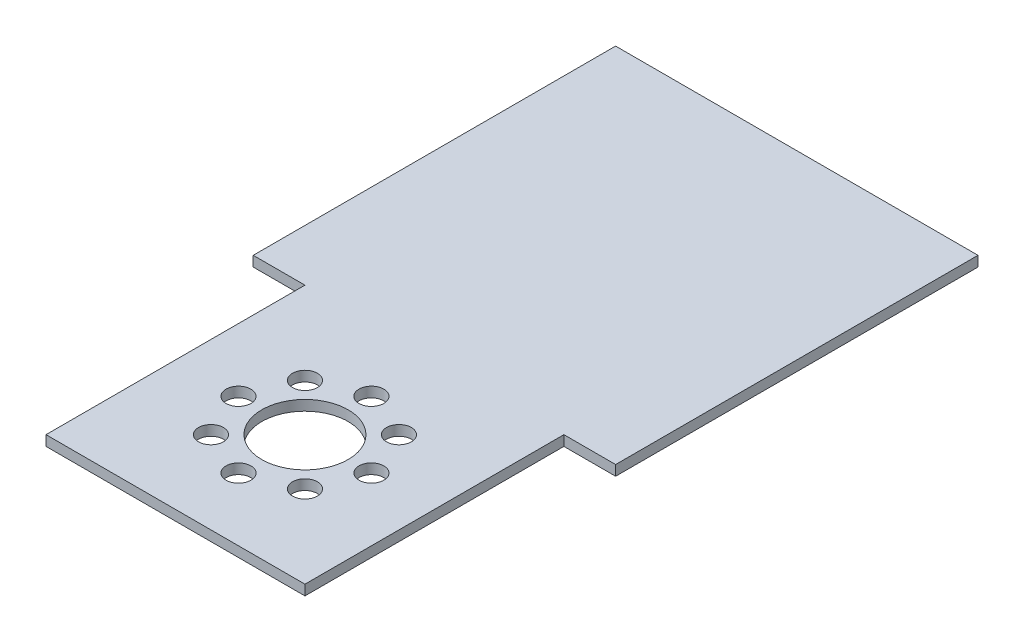
SolidWorks part; units mm, degrees
ref_plane "Front Plane" through (0, 0, 0) normal (0, 0, 1) x (1, 0, 0)
ref_plane "Top Plane" through (0, 0, 0) normal (0, 1, 0) x (1, 0, 0)
ref_plane "Right Plane" through (0, 0, 0) normal (1, 0, 0) x (0, 0, -1)
sketch "Sketch1" plane through (0, 0, 0) normal (0, 1, 0) x (1, 0, 0)
  line L0 (-21.4109, -45.0565) -> (16.6891, -45.0565)
  line L1 (16.6891, -6.9565) -> (24.299, -6.9565)
  line L2 (24.299, -6.9565) -> (24.299, 46.3632)
  line L3 (24.299, 46.3632) -> (-29.0207, 46.3632)
  line L4 (-29.0207, 46.3632) -> (-29.0207, -6.9565)
  line L5 (-29.0207, -6.9565) -> (-21.4109, -6.9565)
  line L6 (-21.4109, -6.9565) -> (-21.4109, -45.0565)
  line L8 (16.6891, -6.9565) -> (16.6891, -45.0565)
  line L9 (-21.4109, -26.0065) -> (16.6891, -26.0065) construction
  line L10 (-2.3609, -45.0565) -> (-2.3609, -26.0065) construction
  line L11 (-2.3609, -26.0065) -> (-2.3609, -6.9565) construction
  circle A0 centre (-9.2757, -19.0917) radius 1.8288
  circle A1 centre (-2.3609, -16.2275) radius 1.8288
  circle A2 centre (-12.1399, -26.0065) radius 1.8288
  circle A3 centre (4.5539, -19.0917) radius 1.8288
  circle A4 centre (7.4181, -26.0065) radius 1.8288
  circle A5 centre (4.5539, -32.9213) radius 1.8288
  circle A6 centre (-2.3609, -35.7855) radius 1.8288
  circle A7 centre (-9.2757, -32.9213) radius 1.8288
  circle A8 centre (-2.3609, -26.0065) radius 6.35
  point P32 (-2.3609, -26.0065)
  point P33 (-9.0208, -31.0865)
  dimension "D8" = 3.6576
  dimension "D10" = 12.7
  dimension "D1" = 53.3197
  dimension "D2" = 53.3197
  dimension "D3" = 38.1
  dimension "D4" = 38.1
  dimension "D5" = 38.1
  dimension "D6" = 7.6098
  dimension "D7" = 9.779
  dimension "D9" = 8
extrude "Boss-Extrude1" add sketch "Sketch1" along normal blind 1.5
